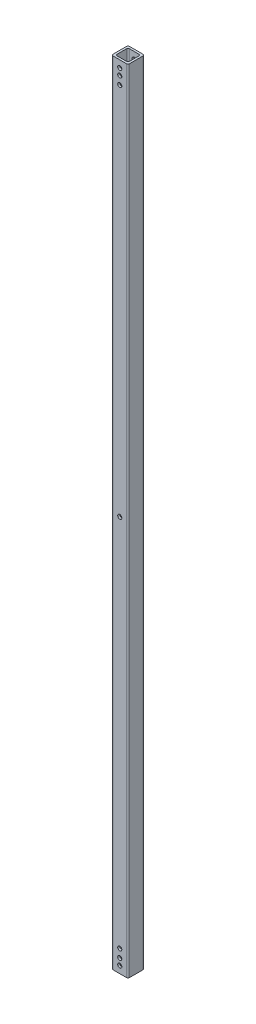
SolidWorks part; units mm, degrees
material "6061-T6 (SS)"
ref_plane "Front Plane" through (0, 0, 0) normal (0, 0, 1) x (1, 0, 0)
ref_plane "Top Plane" through (0, 0, 0) normal (0, 1, 0) x (1, 0, 0)
ref_plane "Right Plane" through (0, 0, 0) normal (1, 0, 0) x (0, 0, -1)
sketch "Sketch1" plane through (0, 0, 0) normal (0, 1, 0) x (1, 0, 0)
  line L0 (9.525, 9.525) -> (-9.525, 9.525)
  line L1 (12.7, -12.7) -> (-12.7, -12.7)
  line L2 (12.7, -12.7) -> (12.7, 12.7)
  line L3 (12.7, 12.7) -> (-12.7, 12.7)
  line L4 (-12.7, -12.7) -> (-12.7, 12.7)
  line L5 (12.7, -12.7) -> (-12.7, 12.7) construction
  line L6 (12.7, 12.7) -> (-12.7, -12.7) construction
  line L7 (-9.525, -9.525) -> (-9.525, 9.525)
  line L8 (9.525, -9.525) -> (-9.525, -9.525)
  line L9 (9.525, -9.525) -> (9.525, 9.525)
  point P0 (0, 0)
  dimension "D1" = 25.4
  dimension "D2" = 25.4
  dimension "D3" = 3.175
extrude "Boss-Extrude1" add sketch "Sketch1" along normal mid plane 1219.2
fillet "Fillet1" radius 2.1082 8 edges at (9.525, 0, -9.525) (-9.525, 0, -9.525) (-9.525, 0, 9.525) (9.525, 0, 9.525) (12.7, 0, -12.7) (-12.7, 0, -12.7) (-12.7, 0, 12.7) (12.7, 0, 12.7)
sketch "Sketch6" plane through (0, 0, -12.7) normal (0, 0, -1) x (-1, 0, 0)
  line L2 (0, 402.295) -> (0, -606.425) construction
  line L4 (0, -609.6) -> (0, 609.6) construction
  line L5 (-10.5918, -609.6) -> (10.5918, -609.6) construction
  line L6 (-10.5918, 609.6) -> (10.5918, 609.6) construction
  line L7 (0, 0) -> (10.5918, 0) construction
  line L8 (10.5918, -609.6) -> (10.5918, 609.6) construction
  circle A0 centre (0, -598.805) radius 3.175
  circle A1 centre (0, -588.645) radius 3.175
  circle A2 centre (0, -575.945) radius 3.175
  circle A3 centre (0, 598.805) radius 3.175
  circle A4 centre (0, 588.645) radius 3.175
  circle A5 centre (0, 575.945) radius 3.175
  point P5 (0, -598.805)
  point P9 (0, -588.645)
  point P10 (0, -575.945)
  dimension "D4" = 6.35
  dimension "D1" = 7.62
  dimension "D2" = 10.16
  dimension "D3" = 12.7
  dimension "D5" = 3.175
extrude "Cut-Extrude5" cut sketch "Sketch6" against normal through all
sketch "Sketch7" plane through (0, 0, -12.7) normal (0, 0, -1) x (-1, 0, 0)
  circle A0 centre (0, 0) radius 3.175
  dimension "D1" = 6.35
extrude "Cut-Extrude6" cut sketch "Sketch7" against normal through all
